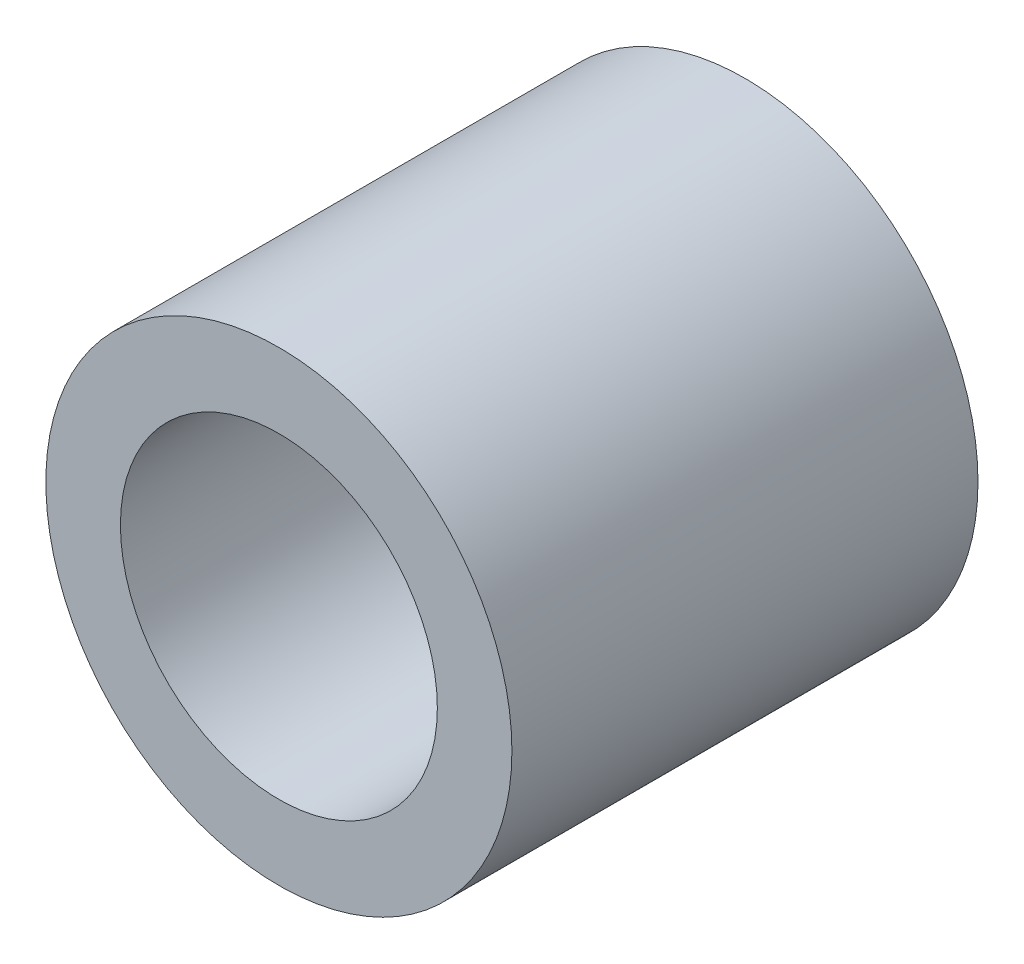
SolidWorks part; units mm, degrees
material "PETG"
ref_plane "Front Plane" through (0, 0, 0) normal (0, 0, 1) x (1, 0, 0)
ref_plane "Top Plane" through (0, 0, 0) normal (0, 1, 0) x (1, 0, 0)
ref_plane "Right Plane" through (0, 0, 0) normal (1, 0, 0) x (0, 0, -1)
sketch "Sketch1" plane through (0, 0, 0) normal (0, 0, 1) x (1, 0, 0)
  circle A0 centre (0, 0) radius 1.7
  circle A1 centre (0, 0) radius 2.5
  dimension "D1" = 3.4
  dimension "D2" = 5
extrude "Boss-Extrude1" add sketch "Sketch1" along normal mid plane 5
